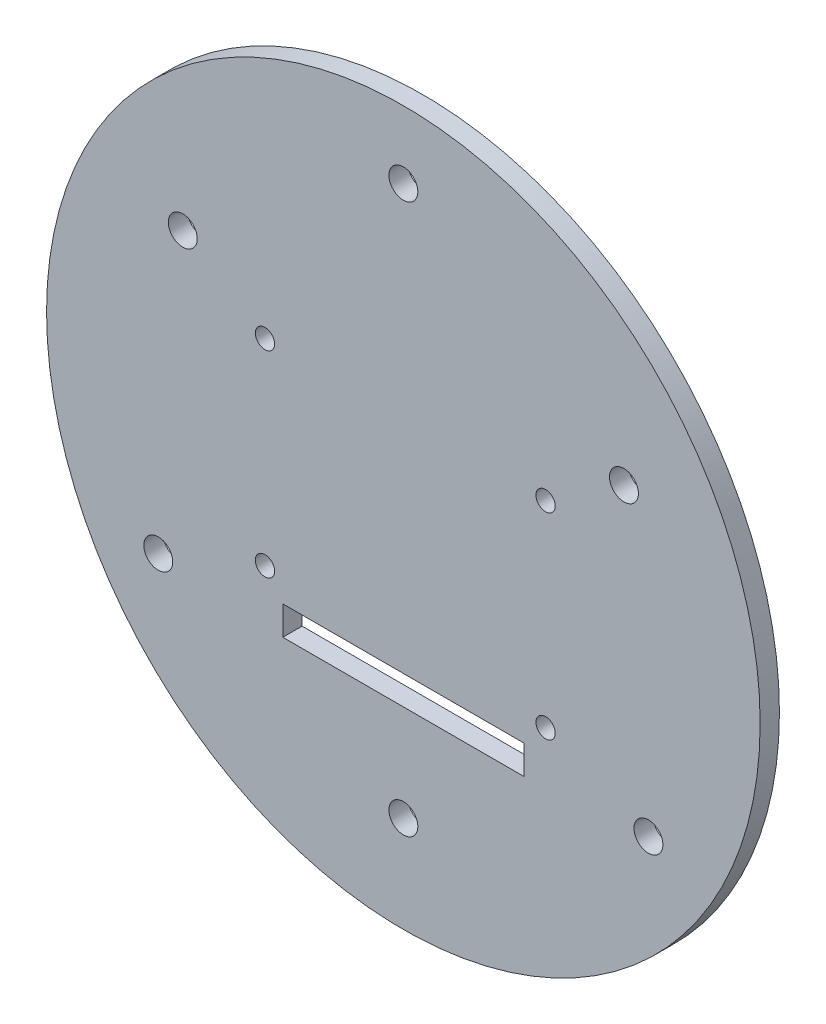
SolidWorks part; units mm, degrees
ref_plane "Plan de face" through (0, 0, 0) normal (0, 0, 1) x (1, 0, 0)
ref_plane "Plan de dessus" through (0, 0, 0) normal (0, 1, 0) x (1, 0, 0)
ref_plane "Plan de droite" through (0, 0, 0) normal (1, 0, 0) x (0, 0, -1)
sketch "Esquisse1" plane through (0, 0, 0) normal (0, 0, 1) x (1, 0, 0)
  line L0 (0, 0) -> (0, -27) construction
  line L1 (0, -27) -> (0, 30) construction
  line L2 (0, 0) -> (25.4165, -15.9375) construction
  line L3 (25.4165, -15.9375) -> (-22.8748, 14.3437) construction
  line L4 (-25.4165, -15.9375) -> (0, 0) construction
  line L5 (0, 0) -> (22.8748, 14.3437) construction
  line L6 (0, 30) -> (25.4165, -15.9375) construction
  line L8 (12.5, -14) -> (-12.5, -14)
  line L9 (12.5, -14) -> (12.5, -17)
  line L10 (12.5, -17) -> (-12.5, -17)
  line L11 (-12.5, -14) -> (-12.5, -17)
  circle A0 centre (0, 0) radius 37
  circle A1 centre (0, 30) radius 1.5
  circle A2 centre (-22.8748, 14.3437) radius 1.5
  circle A3 centre (-25.4165, -15.9375) radius 1.5
  circle A4 centre (0, -27) radius 1.5
  circle A5 centre (25.4165, -15.9375) radius 1.5
  circle A6 centre (22.8748, 14.3437) radius 1.5
  dimension "D1" = 74
  dimension "D11" = 3
  dimension "D12" = 3
  dimension "D13" = 3
  dimension "D14" = 3
  dimension "D15" = 3
  dimension "D16" = 3
  dimension "D2" = 27
  dimension "D3" = 57
  dimension "D4" = 57
  dimension "D5" = 30
  dimension "D6" = 30
  dimension "D7" = 27
  dimension "D8" = 52.5
  dimension "D9" = 52.5
  dimension "D10" = 47.25
  dimension "D17" = 25
  dimension "D18" = 3
  dimension "D19" = 10
  dimension "D20" = 12.5
extrude "Boss.-Extru.1" add sketch "Esquisse1" along normal blind 2
sketch "Esquisse2" plane through (0, 0, 0) normal (0, 0, -1) x (-1, 0, 0)
  line L0 (-16.75, 14.9) -> (-16.75, -13.5)
  line L1 (-12.75, 14.9) -> (12.35, 14.9)
  line L2 (-12.75, 14.9) -> (-12.75, -9.5)
  line L3 (-12.75, -9.5) -> (12.35, -9.5)
  line L4 (12.35, 14.9) -> (12.35, -9.5)
  line L5 (-16.75, -13.5) -> (16.35, -13.5)
  line L6 (16.35, -13.5) -> (16.35, 14.9)
  line L7 (16.35, 14.9) -> (12.35, 14.9)
  line L8 (-16.75, 14.9) -> (-12.75, 14.9)
  point P0 (0, 0)
  dimension "D1" = 25.1
  dimension "D2" = 9.5
  dimension "D3" = 24.4
  dimension "D4" = 4
  dimension "D5" = 4
  dimension "D6" = 4
  dimension "D7" = 12.75
extrude "Boss.-Extru.2" add sketch "Esquisse2" along normal blind 15 contours L8 L0 L5 L6 L7 L4 L3 L2
sketch "Esquisse3" plane through (-12.35, 0, 0) normal (1, 0, 0) x (0, 0, -1)
  line L0 (15, 14.9) -> (0, 14.9) construction
  line L1 (10.625, 14.9) -> (8.625, 14.9)
  line L2 (10.625, 14.9) -> (10.625, -13.5)
  line L3 (10.625, -13.5) -> (8.625, -13.5)
  line L4 (8.625, 14.9) -> (8.625, -13.5)
  line L5 (15, -13.5) -> (0, -13.5) construction
  line L6 (0, 14.9) -> (7.5, 14.9) construction
  line L8 (5.625, 14.9) -> (7.625, 14.9)
  line L9 (5.625, 14.9) -> (5.625, -13.5)
  line L10 (5.625, -13.5) -> (7.625, -13.5)
  line L11 (7.625, 14.9) -> (7.625, -13.5)
  line L12 (8, 14.9) -> (8, -13.5) construction
  dimension "D1" = 2
  dimension "D2" = 0.625
  dimension "D3" = 2
  dimension "D4" = 1
  dimension "D5" = 0.375
  dimension "D6" = 0.5
extrude "Boss.-Extru.3" add sketch "Esquisse3" along normal blind 2.25 contours L11 L10 L9 L8 | L2 L3 L4 L1
sketch "Esquisse5" plane through (12.75, 0, 0) normal (-1, 0, 0) x (0, 0, 1)
  line L1 (-10.625, 14.9) -> (-8.625, 14.9)
  line L2 (-10.625, 14.9) -> (-10.625, -9.5)
  line L3 (-10.625, -9.5) -> (-8.625, -9.5)
  line L4 (-8.625, 14.9) -> (-8.625, -9.5)
  line L5 (-7.625, 14.9) -> (-5.625, 14.9)
  line L6 (-7.625, 14.9) -> (-7.625, -9.5)
  line L7 (-7.625, -9.5) -> (-5.625, -9.5)
  line L8 (-5.625, 14.9) -> (-5.625, -9.5)
extrude "Boss.-Extru.4" add sketch "Esquisse5" along normal blind 2.25
sketch "Esquisse7" plane through (0, 0, -15) normal (0, 0, -1) x (-1, 0, 0)
  line L1 (-16.75, 14.9) -> (16.35, 14.9)
  line L2 (-16.75, 14.9) -> (-16.75, -13.5)
  line L3 (-16.75, -13.5) -> (16.35, -13.5)
  line L4 (16.35, 14.9) -> (16.35, -13.5)
extrude "Boss.-Extru.5" add sketch "Esquisse7" against normal blind 1
sketch "Esquisse8" plane through (0, 0, -15) normal (0, 0, -1) x (-1, 0, 0)
  line L1 (-7.5, 7.5) -> (7.5, 7.5)
  line L2 (-7.5, 7.5) -> (-7.5, -7.5)
  line L3 (-7.5, -7.5) -> (7.5, -7.5)
  line L4 (7.5, 7.5) -> (7.5, -7.5)
  line L5 (-7.5, 7.5) -> (7.5, -7.5) construction
  line L6 (-7.5, -7.5) -> (7.5, 7.5) construction
  point P0 (0, 0)
  dimension "D1" = 15
  dimension "D2" = 15
extrude "Enlèv. mat.-Extru.1" cut sketch "Esquisse8" against normal blind 3 contours L3 L4 L1 L2
sketch "Esquisse9" plane through (0, -13.5, 0) normal (0, -1, 0) x (1, 0, 0)
  line L0 (16.75, 0) -> (-16.35, 0) construction
  line L1 (-10.5, -4.4) -> (10.5, -4.4)
  line L2 (-10.5, -4.4) -> (-10.5, -6.9)
  line L3 (-10.5, -6.9) -> (10.5, -6.9)
  line L4 (10.5, -4.4) -> (10.5, -6.9)
  line L6 (10.5, -4.4) -> (10.5, 0) construction
  line L7 (10.5, 0) -> (-10.5, 0) construction
  line L8 (-10.5, 0) -> (-10.5, -4.4) construction
  point P6 (0, -4.4)
  dimension "D1" = 21
  dimension "D2" = 2.5
  dimension "D3" = 4.4
  dimension "D4" = 0
extrude "Enlèv. mat.-Extru.2" cut sketch "Esquisse9" against normal blind 3 contours L1 L4 L3 L2
sketch "Esquisse10" plane through (0, 0, 2) normal (0, 0, 1) x (1, 0, 0)
  line L0 (16.75, -13.5) -> (-16.35, -13.5) construction
  line L1 (-16.35, -13.5) -> (-16.35, 14.9) construction
  line L2 (16.75, 14.9) -> (16.75, -13.5) construction
  line L3 (16.75, 14.9) -> (12.75, 14.9) construction
  line L4 (-16.35, 14.9) -> (-12.35, 14.9) construction
  circle A0 centre (-14.35, 8.9) radius 1
  circle A1 centre (-14.35, -11.5) radius 1
  circle A2 centre (14.75, -11.5) radius 1
  circle A3 centre (14.75, 8.9) radius 1
  dimension "D1" = 2
  dimension "D2" = 2
  dimension "D3" = 2
  dimension "D4" = 2
  dimension "D5" = 2
  dimension "D6" = 2
  dimension "D7" = 2
  dimension "D8" = 2
  dimension "D9" = 2
  dimension "D10" = 6
  dimension "D11" = 6
  dimension "D12" = 2
extrude "Enlèv. mat.-Extru.3" cut sketch "Esquisse10" against normal blind 19
sketch "Esquisse11" plane through (0, 0, -15) normal (0, 0, -1) x (-1, 0, 0)
  line L1 (16.35, 14.9) -> (-16.75, 14.9)
  line L2 (16.35, 14.9) -> (16.35, -13.5)
  line L3 (16.35, -13.5) -> (-16.75, -13.5)
  line L4 (-16.75, 14.9) -> (-16.75, -13.5)
extrude "Enlèv. mat.-Extru.4" cut sketch "Esquisse11" against normal blind 15
